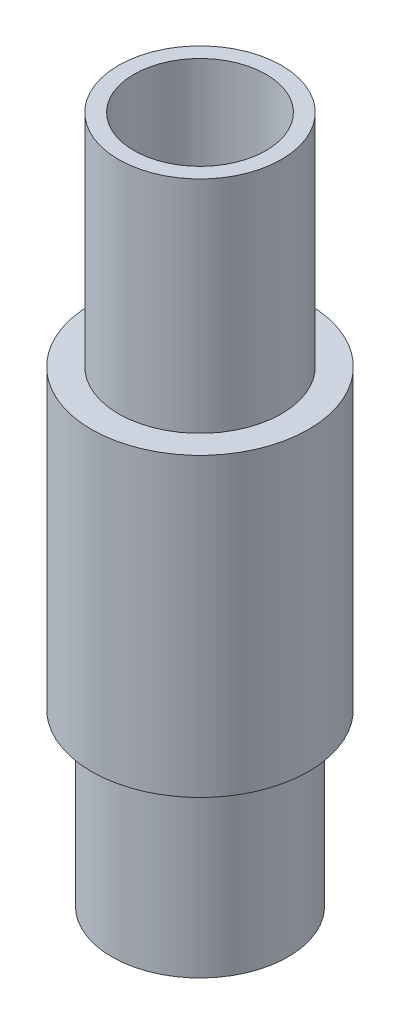
SolidWorks part; units mm, degrees
ref_plane "Front Plane" through (0, 0, 0) normal (0, 0, 1) x (1, 0, 0)
ref_plane "Top Plane" through (0, 0, 0) normal (0, 1, 0) x (1, 0, 0)
ref_plane "Right Plane" through (0, 0, 0) normal (1, 0, 0) x (0, 0, -1)
sketch "Sketch1" plane through (0, 0, 0) normal (0, 0, 1) x (1, 0, 0)
  line L0 (0, 0) -> (0, 68.1682) construction
  line L1 (5.05, 11) -> (5.05, 10)
  line L2 (8, 0) -> (8, 15.5)
  line L3 (6, 1.5398) -> (6, 19.9712) construction
  line L4 (5.05, 11) -> (6, 11.95)
  line L5 (5.8, 0) -> (8, 0)
  line L6 (8, 15.5) -> (9.85, 15.5)
  line L7 (9.85, 15.5) -> (9.85, 42.4)
  line L8 (9.85, 42.4) -> (7.4, 42.4)
  line L9 (7.4, 42.4) -> (7.4, 62.4)
  line L10 (6, 11.95) -> (6, 62.4)
  line L11 (6, 62.4) -> (7.4, 62.4)
  line L12 (5.05, 10) -> (5.85, 10)
  line L13 (5.85, 10) -> (5.8, 0)
  dimension "D1" = 15.5
  dimension "D2" = 26.9
  dimension "D3" = 9.85
  dimension "D4" = 20
  dimension "D5" = 1
  dimension "D6" = 10
revolve "Revolve1" add sketch "Sketch1" angle 360 about L0
